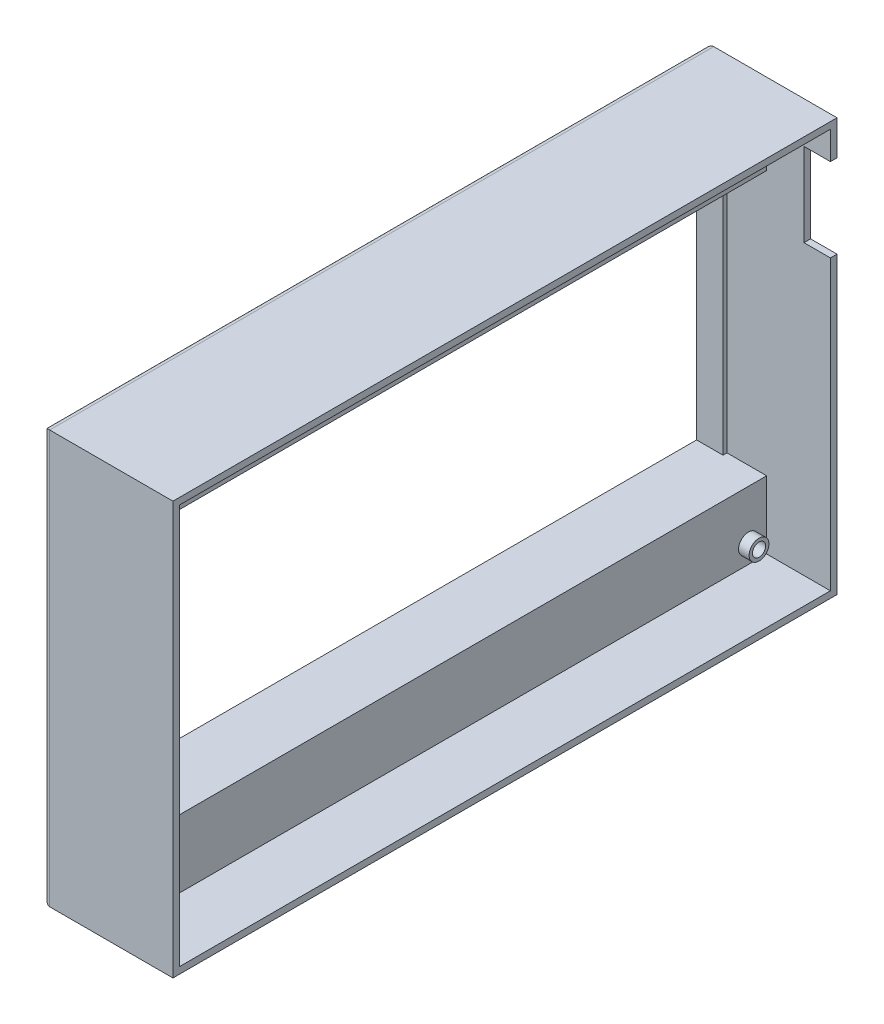
SolidWorks part; units mm, degrees
ref_plane "Front Plane" through (0, 0, 0) normal (0, 0, 1) x (1, 0, 0)
ref_plane "Top Plane" through (0, 0, 0) normal (0, 1, 0) x (1, 0, 0)
ref_plane "Right Plane" through (0, 0, 0) normal (1, 0, 0) x (0, 0, -1)
sketch "Sketch1" plane through (0, 0, 0) normal (1, 0, 0) x (0, 0, -1)
  line L0 (-43.4163, 26.1446) -> (54.5837, 26.1446)
  line L1 (-40.4819, 16.1446) -> (51.6537, 16.1446)
  line L2 (-40.4819, 16.1446) -> (-40.4819, -23.8554)
  line L3 (-40.4819, -23.8554) -> (51.6537, -23.8554)
  line L4 (51.6537, 16.1446) -> (51.6537, -23.8554)
  line L5 (-40.4819, 26.1446) -> (33.7349, 26.1446)
  line L6 (-40.4819, 16.1446) -> (-40.4819, -23.8554)
  line L7 (-40.4819, -33.8554) -> (57.5181, -33.8554)
  line L8 (51.6537, 16.1446) -> (51.6537, -23.8554)
  line L10 (54.5837, 26.1446) -> (54.5837, -33.8554)
  line L11 (54.5837, -33.8554) -> (-43.4163, -33.8554)
  line L12 (-43.4163, 26.1446) -> (-43.4163, -33.8554)
  dimension "D1" = 40
  dimension "D2" = 60
  dimension "D3" = 10
  dimension "D4" = 98
  dimension "D5" = 98
  dimension "D6" = 2.9344
  dimension "D7" = 2.93
extrude "Boss-Extrude2" add sketch "Sketch1" along normal blind 10 contours L0 L12 L11 L7 L10 L1 L4 L3 L2
sketch "Sketch2" plane through (10, 0, 0) normal (1, 0, 0) x (0, 0, -1)
  line L0 (-40.9163, 23.6446) -> (-42.4163, 23.6446) construction
  line L1 (-40.9163, 25.1446) -> (-40.9163, 22.1446) construction
  line L2 (-43.4163, 26.1446) -> (54.5837, 26.1446) construction
  line L4 (5.5837, 26.1446) -> (5.5837, -46.9213) construction
  line L5 (5.5837, -46.9213) -> (54.5837, -3.8554) construction
  line L6 (54.5837, 26.1446) -> (54.5837, -33.8554) construction
  line L7 (54.5837, -3.8554) -> (-48.2991, -3.8554) construction
  line L8 (-43.4163, 26.1446) -> (-43.4163, -33.8554) construction
  circle A0 centre (-40.9163, 23.6446) radius 1.5
  circle A1 centre (52.0837, 23.6446) radius 1.5
  circle A2 centre (52.0837, -31.3554) radius 1.5
  circle A3 centre (-40.9163, -31.3554) radius 1.5
  dimension "D1" = 1
  dimension "D2" = 3
  dimension "D3" = 2.5
  dimension "D4" = 2.5
extrude "Boss-Extrude3" add sketch "Sketch2" along normal blind 1.6
sketch "Sketch3" plane through (11.6, 0, 0) normal (1, 0, 0) x (0, 0, -1)
  circle A0 centre (-40.9163, 23.6446) radius 1
  circle A1 centre (52.0837, 23.6446) radius 1
  circle A2 centre (52.0837, -31.3554) radius 1
  circle A3 centre (-40.9163, -31.3554) radius 1
  dimension "D1" = 2
  dimension "D2" = 2
  dimension "D3" = 2
  dimension "D4" = 2
extrude "Cut-Extrude1" cut sketch "Sketch3" against normal blind 2
sketch "Sketch4" plane through (0, 0, 0) normal (-1, 0, 0) x (0, 0, 1)
  line L0 (-54.5837, 26.1446) -> (-54.5837, -33.8554) construction
  line L1 (-55.8337, 27.3946) -> (44.6663, 27.3946)
  line L2 (-55.8337, 27.3946) -> (-55.8337, -35.1054)
  line L3 (-55.8337, -35.1054) -> (44.6663, -35.1054)
  line L4 (44.6663, 27.3946) -> (44.6663, -35.1054)
  line L5 (43.4163, 26.1446) -> (-54.5837, 26.1446) construction
  line L6 (-54.5837, -33.8554) -> (43.4163, -33.8554) construction
  line L7 (43.4163, 26.1446) -> (43.4163, -33.8554) construction
  line L8 (-54.8337, 26.3946) -> (43.6663, 26.3946)
  line L9 (43.6663, 26.3946) -> (43.6663, -34.1054)
  line L10 (-54.8337, -34.1054) -> (43.6663, -34.1054)
  line L11 (-54.8337, 26.3946) -> (-54.8337, -34.1054)
  dimension "D1" = 1.25
  dimension "D2" = 1.25
  dimension "D3" = 1.25
  dimension "D4" = 1.25
  dimension "D5" = 1
extrude "Boss-Extrude4" add sketch "Sketch4" against normal blind 19.65 separate body
sketch "Sketch5" plane through (0, 0, 0) normal (-1, 0, 0) x (0, 0, 1)
  line L0 (-54.5837, 26.1446) -> (-54.5837, -33.8554) construction
  line L1 (-54.5837, 16.1446) -> (43.4163, 16.1446)
  line L2 (-54.5837, 16.1446) -> (-54.5837, -23.8554)
  line L3 (-54.5837, -23.8554) -> (43.4163, -23.8554)
  line L4 (43.4163, 16.1446) -> (43.4163, -23.8554)
  dimension "D1" = 98
  dimension "D2" = 0
extrude "Cut-Extrude5" cut sketch "Sketch5" against normal blind 14.65
sketch "Sketch6" plane through (0, 0, 0) normal (-1, 0, 0) x (0, 0, 1)
  line L0 (43.6663, -34.1054) -> (43.6663, 26.3946) construction
  line L1 (-54.8337, 26.3946) -> (43.6663, 26.3946)
  line L2 (-54.8337, 26.3946) -> (-54.8337, 16.1446)
  line L3 (-54.8337, 16.1446) -> (43.6663, 16.1446)
  line L4 (43.6663, 26.3946) -> (43.6663, 16.1446)
  line L5 (-54.8337, 26.3946) -> (-54.8337, -34.1054) construction
  line L6 (-54.8337, -23.8554) -> (43.6663, -23.8554)
  line L7 (-54.8337, -23.8554) -> (-54.8337, -34.1054)
  line L8 (-54.8337, -34.1054) -> (43.6663, -34.1054)
  line L9 (43.6663, -23.8554) -> (43.6663, -34.1054)
extrude "Boss-Extrude5" add sketch "Sketch6" against normal blind 10
sketch "Sketch7" plane through (0, 0, 0) normal (-1, 0, 0) x (0, 0, 1)
  line L1 (-54.2337, -24.4397) -> (-54.8337, -24.4397)
  line L2 (-54.2337, -24.4397) -> (-54.2337, 16.1446)
  line L3 (-54.2337, 16.1446) -> (-54.8337, 16.1446)
  line L4 (-54.8337, -24.4397) -> (-54.8337, 16.1446)
  dimension "D1" = 0.6
extrude "Boss-Extrude11" add sketch "Sketch7" against normal blind 4
sketch "Sketch8" plane through (0, 0, 0) normal (-1, 0, 0) x (0, 0, 1)
  line L0 (43.6663, -23.8554) -> (-54.2337, -23.8554) construction
  line L1 (43.0663, -23.8554) -> (43.6663, -23.8554)
  line L2 (43.0663, -23.8554) -> (43.0663, 16.1446)
  line L3 (43.0663, 16.1446) -> (43.6663, 16.1446)
  line L4 (43.6663, -23.8554) -> (43.6663, 16.1446)
  dimension "D1" = 0.6
extrude "Boss-Extrude12" add sketch "Sketch8" against normal blind 4
fillet "Fillet1" radius 1 4 edges at (0, -35.1054, -5.5837) (0, -3.8554, 44.6663) (0, -3.8554, -55.8337) (0, 27.3946, -5.5837)
sketch "Sketch9" plane through (19.65, 0, 0) normal (1, 0, 0) x (0, 0, -1)
  line L0 (54.8337, 26.3946) -> (54.8337, -34.1054) construction
  line L1 (54.8337, 22.1446) -> (47.0337, 22.1446)
  line L3 (54.8337, 12.0246) -> (47.0337, 12.0246)
  line L4 (47.0337, 22.1446) -> (47.0337, 12.0246)
  line L5 (-44.6663, 27.3946) -> (55.8337, 27.3946) construction
  line L6 (54.8337, 22.1446) -> (55.8337, 22.1446)
  line L7 (55.8337, 27.3946) -> (55.8337, -35.1054) construction
  line L8 (55.8337, 22.1446) -> (55.8337, 12.0246)
  line L9 (55.8337, 12.0246) -> (54.8337, 12.0246)
  dimension "D1" = 5.25
  dimension "D3" = 10.12
extrude "Cut-Extrude6" cut sketch "Sketch9" against normal blind 4
sketch "Sketch10" plane through (19.65, 0, 0) normal (1, 0, 0) x (0, 0, -1)
  line L0 (54.8337, 16.1446) -> (54.8337, -23.8554) construction
  line L1 (55.8337, 12.0246) -> (54.8337, 12.0246)
  line L2 (55.8337, 12.0246) -> (55.8337, 9.5246)
  line L3 (55.8337, 9.5246) -> (54.8337, 9.5246)
  line L4 (54.8337, 12.0246) -> (54.8337, 9.5246)
  dimension "D1" = 2.5
extrude "Cut-Extrude8" cut sketch "Sketch10" against normal blind 4
